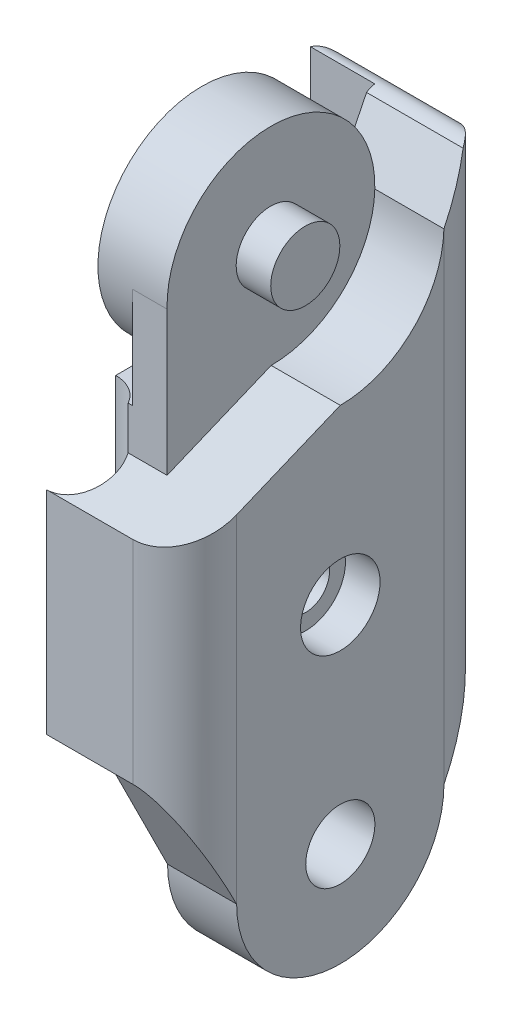
SolidWorks part; units mm, degrees
ref_plane "Front Plane" through (0, 0, 0) normal (0, 0, 1) x (1, 0, 0)
ref_plane "Top Plane" through (0, 0, 0) normal (0, 1, 0) x (1, 0, 0)
ref_plane "Right Plane" through (0, 0, 0) normal (1, 0, 0) x (0, 0, -1)
sketch "Sketch1" plane through (0, 0, 0) normal (0, 1, 0) x (1, 0, 0)
  line L0 (-20.32, 27.0953) -> (-20.32, 11.8553)
  line L1 (0, 27.0953) -> (0, 11.8553)
  line L2 (-16.51, 8.0453) -> (-3.81, 8.0453)
  line L3 (-16.51, 30.9053) -> (-3.81, 30.9053)
  arc A0 (-20.32, 11.8553) -> (-16.51, 8.0453) centre (-16.51, 11.8553) ccw
  arc A1 (-3.81, 8.0453) -> (0, 11.8553) centre (-3.81, 11.8553) ccw
  arc A2 (-20.32, 27.0953) -> (-16.51, 30.9053) centre (-16.51, 27.0953) cw
  arc A3 (0, 27.0953) -> (-3.81, 30.9053) centre (-3.81, 27.0953) ccw
  dimension "D1" = 15.24
  dimension "D2" = 20.32
  dimension "D3" = 22.86
extrude "Boss-Extrude1" add sketch "Sketch1" along normal blind 50.8
sketch "Sketch3" plane through (0, 50.8, 0) normal (0, 1, 0) x (1, 0, 0)
  line L0 (-10.16, 10.5853) -> (-10.16, 28.3653) construction
  line L1 (-16.51, 8.0453) -> (-3.81, 8.0453) construction
  line L2 (-3.81, 30.9053) -> (-16.51, 30.9053) construction
  line L3 (0, 11.8553) -> (0, 27.0953) construction
  circle A0 centre (-10.16, 10.5853) radius 1.27
  circle A1 centre (-10.16, 28.3653) radius 1.27
  dimension "D2" = 2.54
  dimension "D1" = 17.78
  dimension "D3" = 10.16
  dimension "D4" = 2.54
extrude "Cut-Extrude2" cut sketch "Sketch3" against normal blind 50.8
sketch "Sketch2" plane through (-20.32, 0, 0) normal (-1, 0, 0) x (0, 0, 1)
  line L0 (-27.0953, 7.62) -> (-30.9053, 15.24)
  line L1 (-27.0953, 50.8) -> (-27.0953, 0) construction
  line L2 (-30.9053, 15.24) -> (-30.9053, -5.08)
  line L4 (-8.0453, -5.08) -> (-8.0453, 15.24)
  line L5 (-8.0453, 15.24) -> (-11.8553, 7.62)
  line L6 (-11.8553, 50.8) -> (-11.8553, 0) construction
  line L8 (-27.0953, 0) -> (-11.8553, 0) construction
  line L9 (-30.9053, -5.08) -> (-8.0453, -5.08)
  line L10 (-30.9053, 50.8) -> (-30.9053, 0) construction
  line L11 (-8.0453, 50.8) -> (-8.0453, 0) construction
  line L12 (-11.8216, 42.9704) -> (-8.0453, 35.56)
  line L13 (-8.0453, 35.56) -> (-8.0453, 55.88)
  line L14 (-30.9053, 55.88) -> (-30.9053, 35.56)
  line L15 (-30.9053, 35.56) -> (-27.0924, 42.9516)
  line L16 (-8.0453, 55.88) -> (-30.9053, 55.88)
  line L17 (-27.0953, 50.8) -> (-11.8553, 50.8) construction
  arc A0 (-11.8553, 7.62) -> (-27.0953, 7.62) centre (-19.4753, 7.62) cw
  arc A1 (-27.0924, 42.9516) -> (-11.8216, 42.9704) centre (-19.4572, 43.1619) cw
  dimension "D1" = 20.32
  dimension "D2" = 5.08
  dimension "D3" = 20.32
  dimension "D4" = 5.08
extrude "Cut-Extrude1" cut sketch "Sketch2" against normal blind 50.8
sketch "Sketch7" plane through (0, 0, -8.0453) normal (0, 0, 1) x (1, 0, 0)
  line L0 (-15.24, 50.8) -> (-12.7, 50.8)
  line L1 (-12.7, 50.8) -> (-12.7, 35.56)
  line L4 (-7.62, 50.8) -> (-5.08, 50.8)
  line L8 (0, 59.1564) -> (-20.32, 59.1564)
  line L12 (0, 43.9043) -> (0, 7.62) construction
  line L13 (-20.32, 43.9043) -> (-20.32, 7.62) construction
  line L16 (-7.62, 50.8) -> (-7.62, 35.56)
  line L17 (-7.62, 35.56) -> (-12.7, 35.56)
  line L18 (-20.32, 35.56) -> (-15.24, 35.56)
  line L19 (-15.24, 35.56) -> (-15.24, 50.8)
  line L20 (-5.08, 50.8) -> (-5.08, 35.56)
  line L21 (-5.08, 35.56) -> (0, 35.56)
  line L22 (-20.32, 35.56) -> (-20.32, 59.1564)
  line L23 (0, 59.1564) -> (0, 35.56)
  dimension "D3" = 15.24
extrude "Cut-Extrude6" cut sketch "Sketch7" against normal blind 50.8
sketch "Sketch9" plane through (-20.32, 0, 0) normal (-1, 0, 0) x (0, 0, 1)
  line L0 (-19.4753, 35.56) -> (-30.9611, 35.56)
  line L1 (-27.0953, 35.56) -> (-11.8553, 35.56) construction
  line L2 (-30.9611, 35.56) -> (-30.9611, 50.8) construction
  line L4 (-27.0928, 42.9858) -> (-30.9611, 50.8) construction
  line L5 (-30.9611, 35.56) -> (-30.9611, 45.9354)
  line L6 (-27.0928, 42.9858) -> (-29.027, 46.8929)
  arc A0 (-19.4753, 35.56) -> (-27.0928, 42.9858) centre (-19.4753, 43.18) cw
  arc A1 (-30.9611, 45.9354) -> (-29.027, 46.8929) centre (-29.7571, 45.9354) cw
  dimension "D1" = 7.62
  dimension "D2" = 15.24
extrude "Boss-Extrude3" add sketch "Sketch9" against normal blind 20.32
sketch "Sketch4" plane through (0, 0, -8.0453) normal (0, 0, 1) x (1, 0, 0)
  line L0 (-15.24, 15.24) -> (-15.24, 0)
  line L1 (-15.24, 0) -> (-5.08, 0)
  line L2 (-5.08, 0) -> (-5.08, 15.24)
  line L3 (-5.08, 15.24) -> (-15.24, 15.24)
  line L4 (0, 0) -> (0, 7.62) construction
  dimension "D1" = 10.16
  dimension "D2" = 5.08
  dimension "D3" = 15.24
extrude "Cut-Extrude3" cut sketch "Sketch4" against normal blind 50.8
sketch "Sketch5" plane through (-20.32, 0, 0) normal (-1, 0, 0) x (0, 0, 1)
  line L0 (-27.0953, 35.56) -> (-27.0953, 7.62) construction
  circle A0 centre (-19.4753, 7.62) radius 2.54
  arc A1 (-27.0953, 7.62) -> (-11.8553, 7.62) centre (-19.4753, 7.62) ccw construction
  point P5 (-19.4753, 0)
  dimension "D3" = 5.08
  dimension "D1" = 7.62
  dimension "D2" = 7.62
extrude "Cut-Extrude5" cut sketch "Sketch5" against normal blind 50.8
sketch "Sketch8" plane through (-15.24, 0, 0) normal (-1, 0, 0) x (0, 0, 1)
  circle A0 centre (-19.4416, 43.18) radius 2.54
  arc A1 (-11.8216, 42.9704) -> (-27.0933, 42.9867) centre (-19.4572, 43.1619) ccw construction
  point P6 (-19.4491, 50.8)
  dimension "D1" = 5.08
  dimension "D2" = 7.62
  dimension "D3" = 7.62
extrude "Boss-Extrude2" add sketch "Sketch8" along normal blind 2.54
pattern_linear "LPattern1" count 2 spacing 12.7 along (1, 0, 0) of "Boss-Extrude2"
sketch "Sketch10" plane through (0, 35.56, 0) normal (0, -1, 0) x (1, 0, 0)
  line L0 (-16.51, -30.9053) -> (-3.81, -30.9053)
  line L1 (0, -27.0953) -> (5.7709, -37.2588)
  line L2 (5.7709, -37.2588) -> (-26.7978, -37.8907)
  line L3 (-26.7978, -37.8907) -> (-20.32, -27.0953)
  arc A0 (-3.81, -30.9053) -> (0, -27.0953) centre (-3.81, -27.0953) ccw
  arc A1 (-16.51, -30.9053) -> (-20.32, -27.0953) centre (-16.51, -27.0953) cw
extrude "Cut-Extrude7" cut sketch "Sketch10" against normal blind 20.32
sketch "Sketch12" plane through (0, 0, -8.0453) normal (0, 0, 1) x (1, 0, 0)
  line L0 (-12.7, 35.56) -> (-7.62, 35.56)
  line L1 (-12.7, 35.56) -> (-12.7, 55.5014)
  line L2 (-7.62, 35.56) -> (-7.62, 55.5014)
  line L3 (-12.7, 55.5014) -> (-7.62, 55.5014)
extrude "Cut-Extrude8" cut sketch "Sketch12" against normal blind 21.59
sketch "Sketch13" plane through (-20.32, 0, 0) normal (-1, 0, 0) x (0, 0, 1)
  line L0 (-19.4753, 35.56) -> (-8.0453, 30.8255)
  line L1 (-19.4753, 35.56) -> (-11.8553, 35.56) construction
  line L2 (-19.4753, 35.56) -> (-1.3207, 35.56)
  line L3 (-1.3207, 35.56) -> (-1.3207, 30.8255)
  line L4 (-1.3207, 30.8255) -> (-8.0453, 30.8255)
  line L5 (-8.0453, 35.56) -> (-8.0453, 15.24) construction
extrude "Cut-Extrude9" cut sketch "Sketch13" against normal blind 5.08
pattern_linear "LPattern2" count 2 spacing 15.24 along (1, 0, 0) of "Cut-Extrude9"
sketch "Sketch15" plane through (0, 35.56, 0) normal (0, 1, 0) x (1, 0, 0)
  line L0 (-10.16, 25.8253) -> (-10.16, 13.1253)
  line L1 (-12.7, 8.0453) -> (-7.62, 8.0453) construction
  line L2 (-10.16, 30.9053) -> (-44.0958, 43.9632)
  line L3 (-44.0958, 43.9632) -> (-39.9737, -4.467)
  line L4 (-39.9737, -4.467) -> (-10.16, 8.0453)
  line L5 (-5.08, 30.9053) -> (-15.24, 30.9053) construction
  arc A0 (-10.16, 25.8253) -> (-10.16, 30.9053) centre (-10.16, 28.3653) cw
  arc A1 (-10.16, 13.1253) -> (-10.16, 8.0453) centre (-10.16, 10.5853) cw
  circle A2 centre (-10.16, 28.3653) radius 1.27 construction
  circle A3 centre (-10.16, 10.5853) radius 1.27 construction
extrude "Cut-Extrude10" cut sketch "Sketch15" against normal mid plane 81.534
sketch "Sketch16" plane through (-7.62, 0, 0) normal (-1, 0, 0) x (0, 0, 1)
  circle A0 centre (-19.4572, 43.1619) radius 7.6381
  arc A1 (-11.8216, 42.9704) -> (-27.0933, 42.9867) centre (-19.4572, 43.1619) ccw construction
extrude "Boss-Extrude4" add sketch "Sketch16" along normal blind 2.54
sketch "Sketch17" plane through (-10.16, 0, 0) normal (-1, 0, 0) x (0, 0, 1)
  circle A0 centre (-19.4572, 43.1619) radius 2.54
  arc A1 (-18.7149, 35.56) -> (-20.1996, 35.56) centre (-19.4572, 43.1619) ccw construction
  dimension "D1" = 5.08
extrude "Cut-Extrude11" cut sketch "Sketch17" against normal blind 2.54
sketch "Sketch23" plane through (-5.08, 0, 0) normal (1, 0, 0) x (0, 0, -1)
  line L0 (11.8216, 42.9704) -> (11.8216, 35.56)
  line L1 (11.8216, 42.9704) -> (8.0453, 42.9704)
  line L2 (11.8216, 35.56) -> (8.0453, 35.56)
  line L3 (8.0453, 42.9704) -> (8.0453, 35.56)
extrude "Cut-Extrude16" cut sketch "Sketch23" against normal blind 2.54
sketch "Sketch24" plane through (-5.08, 0, 0) normal (1, 0, 0) x (0, 0, -1)
  line L0 (8.0453, 35.56) -> (11.8216, 35.56)
  line L1 (11.8216, 35.56) -> (11.8216, 32.3897)
  line L2 (19.4753, 35.56) -> (8.0453, 30.8255) construction
  line L3 (11.8216, 32.3897) -> (8.0453, 30.8255)
  line L4 (8.0453, 30.8255) -> (8.0453, 35.56)
extrude "Cut-Extrude17" cut sketch "Sketch24" against normal blind 9.906
sketch "Sketch25" plane through (-10.16, 0, 0) normal (-1, 0, 0) x (0, 0, 1)
  line L0 (-13.1253, 15.24) -> (-13.1253, 35.56) construction
  line L1 (-13.1253, 15.24) -> (-25.8253, 15.24) construction
  circle A0 centre (-19.4753, 22.86) radius 1.7526
  point P2 (0, 0)
  point P5 (0, 0)
  dimension "D3" = 3.5052
  dimension "D1" = 6.35
  dimension "D2" = 7.62
extrude "Cut-Extrude18" cut sketch "Sketch25" against normal blind 20.828
sketch "Sketch26" plane through (0, 0, 0) normal (1, 0, 0) x (0, 0, -1)
  circle A0 centre (19.4753, 22.86) radius 2.921
  dimension "D1" = 5.842
extrude "Cut-Extrude19" cut sketch "Sketch26" against normal blind 2.54
